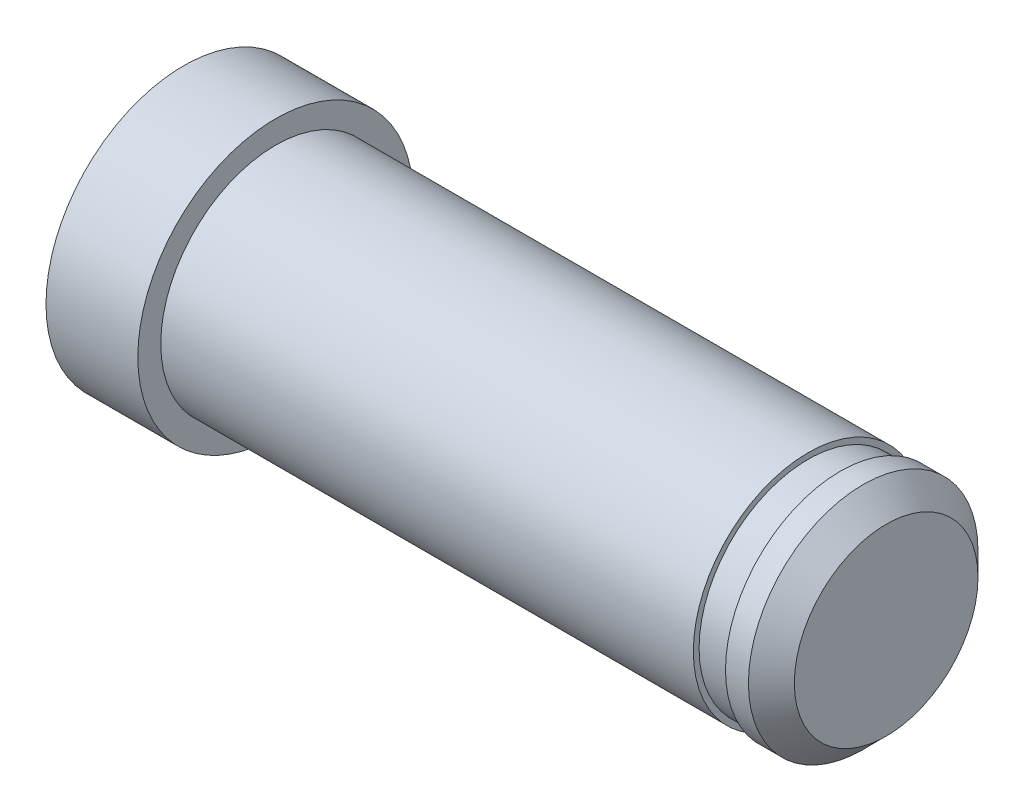
SolidWorks part; units mm, degrees
material "6061 合金"
ref_plane "Front" through (0, 0, 0) normal (0, 0, 1) x (1, 0, 0)
ref_plane "Top" through (0, 0, 0) normal (0, 1, 0) x (1, 0, 0)
ref_plane "Right" through (0, 0, 0) normal (1, 0, 0) x (0, 0, -1)
sketch "草图1" plane through (0, 0, 0) normal (0, 0, 1) x (1, 0, 0)
  line L0 (-15.3, 0) -> (0.7915, 0) construction
  line L1 (-15.3, 0) -> (0, 0)
  line L2 (-15.3, 0) -> (-15.3, 3)
  line L4 (0, 0) -> (0, 2.5)
  line L5 (-13.3, 2.5) -> (-1.7, 2.5)
  line L10 (-1, 2.5) -> (0, 2.5)
  line L12 (-1.7, 2.5) -> (-1.7, 2.375)
  line L13 (-1.7, 2.375) -> (-1, 2.375)
  line L14 (-1, 2.5) -> (-1, 2.375)
  line L15 (-13.3, 2.5) -> (-13.3, 3)
  line L16 (-13.3, 3) -> (-15.3, 3)
  point P2 (-13.3, 2.75)
  dimension "D1" = 2.5
  dimension "D2" = 13.3
  dimension "D3" = 2.375
  dimension "D4" = 2
  dimension "D5" = 0.7
  dimension "D6" = 3
  dimension "D7" = 1
revolve "旋转1" add sketch "草图1" angle 360 about L0
chamfer "倒角1" distance 0.5 angle 45 1 edges at (0, 0, 2.5)
